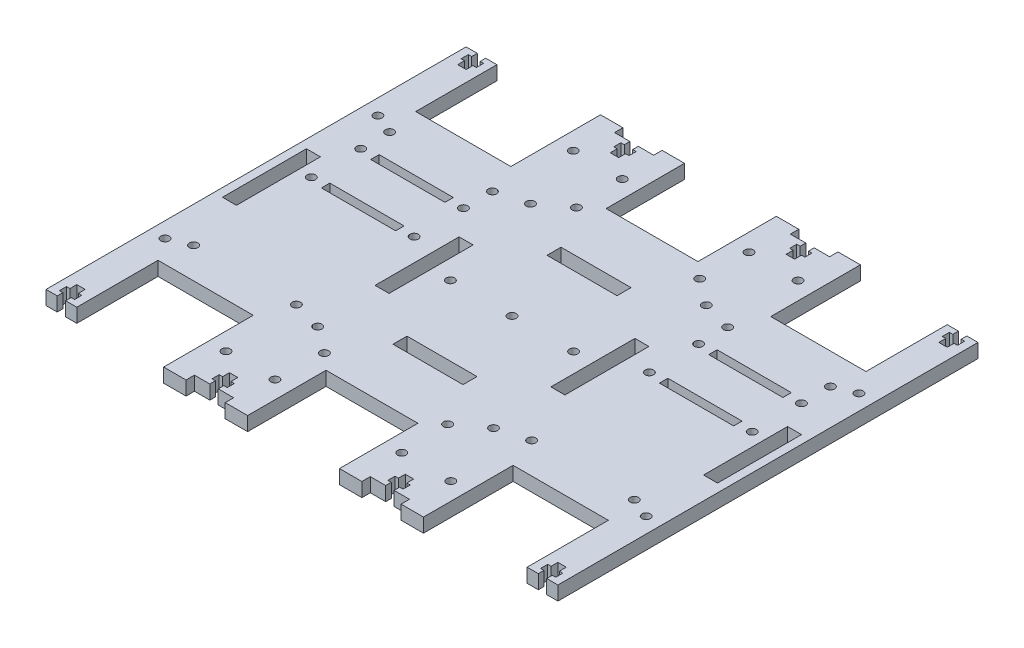
SolidWorks part; units mm, degrees
ref_plane "Front Plane" through (0, 0, 0) normal (0, 0, 1) x (1, 0, 0)
ref_plane "Top Plane" through (0, 0, 0) normal (0, 1, 0) x (1, 0, 0)
ref_plane "Right Plane" through (0, 0, 0) normal (1, 0, 0) x (0, 0, -1)
sketch "Sketch1" plane through (0, 0, 0) normal (0, 0, 1) x (1, 0, 0)
  line L0 (-91.394, 32.0854) -> (-91.394, 72.0854) construction
  line L1 (-91.394, 62.0854) -> (-80.394, 62.0854)
  line L2 (-91.394, 62.0854) -> (-91.394, 57.0854)
  line L3 (-91.394, 57.0854) -> (-80.394, 57.0854)
  line L4 (-80.394, 62.0854) -> (-80.394, 57.0854)
  line L5 (91.394, 72.0854) -> (91.394, 32.0854) construction
  line L6 (-46.394, 62.0854) -> (-16.394, 62.0854)
  line L7 (-46.394, 62.0854) -> (-46.394, 57.0854)
  line L8 (-46.394, 57.0854) -> (-16.394, 57.0854)
  line L9 (-16.394, 62.0854) -> (-16.394, 57.0854)
  line L10 (16.394, 62.0854) -> (46.394, 62.0854)
  line L11 (16.394, 62.0854) -> (16.394, 57.0854)
  line L12 (16.394, 57.0854) -> (46.394, 57.0854)
  line L13 (46.394, 62.0854) -> (46.394, 57.0854)
  line L14 (80.394, 62.0854) -> (91.394, 62.0854)
  line L15 (80.394, 62.0854) -> (80.394, 57.0854)
  line L16 (80.394, 57.0854) -> (91.394, 57.0854)
  line L17 (91.394, 62.0854) -> (91.394, 57.0854)
  line L18 (-80.394, 62.0854) -> (-46.394, 62.0854) construction
  line L19 (-16.394, 62.0854) -> (16.394, 62.0854) construction
  line L20 (46.394, 62.0854) -> (80.394, 62.0854) construction
  line L21 (-91.394, 72.0854) -> (91.394, 72.0854) construction
  line L22 (0, 72.0854) -> (0, 62.0854) construction
  dimension "D1" = 5
  dimension "D2" = 11
  dimension "D3" = 10
  dimension "D4" = 34
  dimension "D5" = 30
extrude "Boss-Extrude1" add sketch "Sketch1" along normal blind 25
sketch "Sketch2" plane through (0, 0, 25) normal (0, 0, 1) x (1, 0, 0)
  line L1 (-91.394, 62.0854) -> (91.394, 62.0854)
  line L2 (-91.394, 62.0854) -> (-91.394, 57.0854)
  line L3 (-91.394, 57.0854) -> (91.394, 57.0854)
  line L4 (91.394, 62.0854) -> (91.394, 57.0854)
extrude "Boss-Extrude4" add sketch "Sketch2" along normal blind 100
sketch "Sketch3" plane through (0, 0, 125) normal (0, 0, 1) x (1, 0, 0)
  line L4 (46.394, 62.0854) -> (16.394, 62.0854)
  line L5 (46.394, 57.0854) -> (46.394, 62.0854)
  line L6 (16.394, 57.0854) -> (46.394, 57.0854)
  line L7 (16.394, 62.0854) -> (16.394, 57.0854)
  line L8 (46.394, 62.0854) -> (16.394, 62.0854)
  line L9 (46.394, 57.0854) -> (46.394, 62.0854)
  line L10 (16.394, 57.0854) -> (46.394, 57.0854)
  line L11 (16.394, 62.0854) -> (16.394, 57.0854)
  line L12 (-16.394, 62.0854) -> (-46.394, 62.0854)
  line L13 (-16.394, 57.0854) -> (-16.394, 62.0854)
  line L14 (-46.394, 57.0854) -> (-16.394, 57.0854)
  line L15 (-46.394, 62.0854) -> (-46.394, 57.0854)
  line L16 (-16.394, 62.0854) -> (-46.394, 62.0854)
  line L17 (-16.394, 57.0854) -> (-16.394, 62.0854)
  line L18 (-46.394, 57.0854) -> (-16.394, 57.0854)
  line L19 (-46.394, 62.0854) -> (-46.394, 57.0854)
  line L20 (-80.394, 62.0854) -> (-91.394, 62.0854)
  line L21 (-80.394, 57.0854) -> (-80.394, 62.0854)
  line L22 (-91.394, 57.0854) -> (-80.394, 57.0854)
  line L23 (-91.394, 62.0854) -> (-91.394, 57.0854)
  line L24 (-80.394, 62.0854) -> (-91.394, 62.0854)
  line L25 (-80.394, 57.0854) -> (-80.394, 62.0854)
  line L26 (-91.394, 57.0854) -> (-80.394, 57.0854)
  line L27 (-91.394, 62.0854) -> (-91.394, 57.0854)
  line L28 (91.394, 62.0854) -> (80.394, 62.0854)
  line L29 (80.394, 62.0854) -> (80.394, 57.0854)
  line L30 (80.394, 57.0854) -> (91.394, 57.0854)
  line L31 (91.394, 57.0854) -> (91.394, 62.0854)
  line L32 (91.394, 62.0854) -> (80.394, 62.0854)
  line L33 (80.394, 62.0854) -> (80.394, 57.0854)
  line L34 (80.394, 57.0854) -> (91.394, 57.0854)
  line L35 (91.394, 57.0854) -> (91.394, 62.0854)
  dimension "D1" = 0
  dimension "D2" = 0
  dimension "D3" = 0
  dimension "D4" = 0
extrude "Boss-Extrude5" add sketch "Sketch3" along normal blind 25
sketch "Sketch4" plane through (0, 62.0854, 0) normal (0, 1, 0) x (1, 0, 0)
  line L0 (85.894, 0) -> (85.894, -12.8544) construction
  line L1 (91.394, 0) -> (80.394, 0) construction
  line L2 (84.394, -2) -> (83.169, -2)
  line L3 (87.394, -7) -> (84.394, -7)
  line L4 (87.394, -7) -> (87.394, -4.55)
  line L5 (87.394, 0) -> (84.394, 0)
  line L6 (84.394, -7) -> (84.394, -4.55)
  line L7 (87.394, -7) -> (84.394, 0) construction
  line L8 (87.394, 0) -> (84.394, -7) construction
  line L9 (88.619, -2) -> (87.394, -2)
  line L10 (88.619, -2) -> (88.619, -4.55)
  line L11 (88.619, -4.55) -> (87.394, -4.55)
  line L12 (83.169, -2) -> (83.169, -4.55)
  line L13 (88.619, -2) -> (83.169, -4.55) construction
  line L14 (88.619, -4.55) -> (83.169, -2) construction
  line L15 (84.394, -2) -> (84.394, 0)
  line L16 (84.394, -4.55) -> (83.169, -4.55)
  line L17 (87.394, -2) -> (87.394, 0)
  line L18 (31.394, 0) -> (31.394, -22.5129) construction
  line L19 (46.394, 0) -> (16.394, 0) construction
  line L20 (85.894, -12.8544) -> (31.394, -12.8544) construction
  line L21 (58.644, -12.8544) -> (58.644, 12.1198) construction
  line L22 (28.669, -4.55) -> (34.119, -2) construction
  line L23 (28.669, -2) -> (34.119, -4.55) construction
  line L24 (29.894, 0) -> (32.894, -7) construction
  line L25 (29.894, -7) -> (32.894, 0) construction
  line L26 (29.894, -2) -> (29.894, 0)
  line L27 (32.894, -4.55) -> (34.119, -4.55)
  line L28 (32.894, -2) -> (32.894, 0)
  line L29 (34.119, -2) -> (34.119, -4.55)
  line L30 (28.669, -4.55) -> (29.894, -4.55)
  line L31 (28.669, -2) -> (28.669, -4.55)
  line L32 (28.669, -2) -> (29.894, -2)
  line L33 (32.894, -7) -> (32.894, -4.55)
  line L34 (29.894, 0) -> (32.894, 0)
  line L35 (29.894, -7) -> (29.894, -4.55)
  line L36 (29.894, -7) -> (32.894, -7)
  line L37 (32.894, -2) -> (34.119, -2)
  line L38 (0, -25) -> (0, 26.5312) construction
  line L39 (16.394, -25) -> (-16.394, -25) construction
  line L40 (-88.619, -4.55) -> (-83.169, -2) construction
  line L41 (-88.619, -2) -> (-83.169, -4.55) construction
  line L42 (-87.394, 0) -> (-84.394, -7) construction
  line L43 (-87.394, -7) -> (-84.394, 0) construction
  line L44 (-87.394, -2) -> (-87.394, 0)
  line L45 (-84.394, -4.55) -> (-83.169, -4.55)
  line L46 (-84.394, -2) -> (-84.394, 0)
  line L47 (-83.169, -2) -> (-83.169, -4.55)
  line L48 (-88.619, -4.55) -> (-87.394, -4.55)
  line L49 (-88.619, -2) -> (-88.619, -4.55)
  line L50 (-88.619, -2) -> (-87.394, -2)
  line L51 (-84.394, -7) -> (-84.394, -4.55)
  line L52 (-87.394, 0) -> (-84.394, 0)
  line L53 (-87.394, -7) -> (-87.394, -4.55)
  line L54 (-87.394, -7) -> (-84.394, -7)
  line L55 (-84.394, -2) -> (-83.169, -2)
  line L56 (-29.894, -7) -> (-32.894, 0) construction
  line L57 (-29.894, 0) -> (-32.894, -7) construction
  line L58 (-28.669, -2) -> (-34.119, -4.55) construction
  line L59 (-28.669, -4.55) -> (-34.119, -2) construction
  line L60 (-32.894, -2) -> (-34.119, -2)
  line L61 (-29.894, -7) -> (-32.894, -7)
  line L62 (-29.894, -7) -> (-29.894, -4.55)
  line L63 (-29.894, 0) -> (-32.894, 0)
  line L64 (-32.894, -7) -> (-32.894, -4.55)
  line L65 (-28.669, -2) -> (-29.894, -2)
  line L66 (-28.669, -2) -> (-28.669, -4.55)
  line L67 (-28.669, -4.55) -> (-29.894, -4.55)
  line L68 (-34.119, -2) -> (-34.119, -4.55)
  line L69 (-32.894, -2) -> (-32.894, 0)
  line L70 (-32.894, -4.55) -> (-34.119, -4.55)
  line L71 (-29.894, -2) -> (-29.894, 0)
  line L72 (91.394, -75) -> (-91.394, -75) construction
  line L73 (91.394, -150) -> (91.394, 0) construction
  line L74 (-91.394, -150) -> (-91.394, 0) construction
  line L75 (-28.669, -145.45) -> (-34.119, -148) construction
  line L76 (-28.669, -148) -> (-34.119, -145.45) construction
  line L77 (-29.894, -150) -> (-32.894, -143) construction
  line L78 (-29.894, -143) -> (-32.894, -150) construction
  line L79 (-87.394, -143) -> (-84.394, -150) construction
  line L80 (-87.394, -150) -> (-84.394, -143) construction
  line L81 (-88.619, -148) -> (-83.169, -145.45) construction
  line L82 (-88.619, -145.45) -> (-83.169, -148) construction
  line L83 (29.894, -143) -> (32.894, -150) construction
  line L84 (29.894, -150) -> (32.894, -143) construction
  line L85 (28.669, -148) -> (34.119, -145.45) construction
  line L86 (28.669, -145.45) -> (34.119, -148) construction
  line L87 (85.894, -137.1456) -> (31.394, -137.1456) construction
  line L88 (88.619, -145.45) -> (83.169, -148) construction
  line L89 (88.619, -148) -> (83.169, -145.45) construction
  line L90 (87.394, -150) -> (84.394, -143) construction
  line L91 (87.394, -143) -> (84.394, -150) construction
  line L92 (85.894, -150) -> (85.894, -137.1456) construction
  line L93 (-29.894, -148) -> (-29.894, -150)
  line L94 (-32.894, -145.45) -> (-34.119, -145.45)
  line L95 (-32.894, -148) -> (-32.894, -150)
  line L96 (-34.119, -148) -> (-34.119, -145.45)
  line L97 (-28.669, -145.45) -> (-29.894, -145.45)
  line L98 (-28.669, -148) -> (-28.669, -145.45)
  line L99 (-28.669, -148) -> (-29.894, -148)
  line L100 (-32.894, -143) -> (-32.894, -145.45)
  line L101 (-29.894, -150) -> (-32.894, -150)
  line L102 (-29.894, -143) -> (-29.894, -145.45)
  line L103 (-29.894, -143) -> (-32.894, -143)
  line L104 (-32.894, -148) -> (-34.119, -148)
  line L105 (-84.394, -148) -> (-83.169, -148)
  line L106 (-87.394, -143) -> (-84.394, -143)
  line L107 (-87.394, -143) -> (-87.394, -145.45)
  line L108 (-87.394, -150) -> (-84.394, -150)
  line L109 (-84.394, -143) -> (-84.394, -145.45)
  line L110 (-88.619, -148) -> (-87.394, -148)
  line L111 (-88.619, -148) -> (-88.619, -145.45)
  line L112 (-88.619, -145.45) -> (-87.394, -145.45)
  line L113 (-83.169, -148) -> (-83.169, -145.45)
  line L114 (-84.394, -148) -> (-84.394, -150)
  line L115 (-84.394, -145.45) -> (-83.169, -145.45)
  line L116 (-87.394, -148) -> (-87.394, -150)
  line L117 (32.894, -148) -> (34.119, -148)
  line L118 (29.894, -143) -> (32.894, -143)
  line L119 (29.894, -143) -> (29.894, -145.45)
  line L120 (29.894, -150) -> (32.894, -150)
  line L121 (32.894, -143) -> (32.894, -145.45)
  line L122 (28.669, -148) -> (29.894, -148)
  line L123 (28.669, -148) -> (28.669, -145.45)
  line L124 (28.669, -145.45) -> (29.894, -145.45)
  line L125 (34.119, -148) -> (34.119, -145.45)
  line L126 (32.894, -148) -> (32.894, -150)
  line L127 (32.894, -145.45) -> (34.119, -145.45)
  line L128 (29.894, -148) -> (29.894, -150)
  line L129 (87.394, -148) -> (87.394, -150)
  line L130 (84.394, -145.45) -> (83.169, -145.45)
  line L131 (84.394, -148) -> (84.394, -150)
  line L132 (83.169, -148) -> (83.169, -145.45)
  line L133 (88.619, -145.45) -> (87.394, -145.45)
  line L134 (88.619, -148) -> (88.619, -145.45)
  line L135 (88.619, -148) -> (87.394, -148)
  line L136 (84.394, -143) -> (84.394, -145.45)
  line L137 (87.394, -150) -> (84.394, -150)
  line L138 (87.394, -143) -> (87.394, -145.45)
  line L139 (87.394, -143) -> (84.394, -143)
  line L140 (84.394, -148) -> (83.169, -148)
  point P4 (85.894, -3.5)
  point P9 (85.894, -3.275)
  point P37 (31.394, -3.275)
  point P38 (31.394, -3.5)
  point P56 (-85.894, -3.275)
  point P57 (-85.894, -3.5)
  point P70 (-31.394, -3.5)
  point P71 (-31.394, -3.275)
  point P129 (-31.394, -146.725)
  point P130 (-31.394, -146.5)
  point P131 (-85.894, -146.5)
  point P132 (-85.894, -146.725)
  point P133 (31.394, -146.5)
  point P134 (31.394, -146.725)
  point P135 (85.894, -146.725)
  point P136 (85.894, -146.5)
  dimension "D1" = 7
  dimension "D2" = 3
  dimension "D3" = 5.45
  dimension "D4" = 2.55
  dimension "D5" = 2
extrude "Cut-Extrude1" cut sketch "Sketch4" against normal through all
sketch "Sketch5" plane through (0, 0, 0) normal (0, 0, -1) x (-1, 0, 0)
  line L0 (-32.894, 57.0854) -> (-46.394, 57.0854) construction
  line L1 (-46.394, 62.0854) -> (-38.394, 62.0854)
  line L2 (-46.394, 62.0854) -> (-46.394, 57.0854)
  line L3 (-46.394, 57.0854) -> (-38.394, 57.0854)
  line L4 (-38.394, 62.0854) -> (-38.394, 57.0854)
  line L5 (46.394, 57.0854) -> (32.894, 57.0854) construction
  line L6 (-16.394, 62.0854) -> (-24.394, 62.0854)
  line L7 (-16.394, 62.0854) -> (-16.394, 57.0854)
  line L8 (-16.394, 57.0854) -> (-24.394, 57.0854)
  line L9 (-24.394, 62.0854) -> (-24.394, 57.0854)
  line L10 (16.394, 62.0854) -> (24.394, 62.0854)
  line L11 (16.394, 62.0854) -> (16.394, 57.0854)
  line L12 (16.394, 57.0854) -> (24.394, 57.0854)
  line L13 (24.394, 62.0854) -> (24.394, 57.0854)
  line L14 (46.394, 62.0854) -> (38.394, 62.0854)
  line L15 (46.394, 62.0854) -> (46.394, 57.0854)
  line L16 (46.394, 57.0854) -> (38.394, 57.0854)
  line L17 (38.394, 62.0854) -> (38.394, 57.0854)
  line L18 (29.894, 57.0854) -> (16.394, 57.0854) construction
  line L19 (-16.394, 57.0854) -> (-29.894, 57.0854) construction
  dimension "D1" = 8
  dimension "D2" = 8
extrude "Boss-Extrude6" add sketch "Sketch5" along normal blind 3
sketch "Sketch6" plane through (0, 0, 150) normal (0, 0, 1) x (1, 0, 0)
  line L4 (-16.394, 62.0854) -> (-24.394, 62.0854)
  line L5 (-24.394, 62.0854) -> (-24.394, 57.0854)
  line L6 (-24.394, 57.0854) -> (-16.394, 57.0854)
  line L7 (-16.394, 57.0854) -> (-16.394, 62.0854)
  line L8 (-16.394, 62.0854) -> (-24.394, 62.0854)
  line L9 (-24.394, 62.0854) -> (-24.394, 57.0854)
  line L10 (-24.394, 57.0854) -> (-16.394, 57.0854)
  line L11 (-16.394, 57.0854) -> (-16.394, 62.0854)
  line L12 (24.394, 62.0854) -> (16.394, 62.0854)
  line L13 (24.394, 57.0854) -> (24.394, 62.0854)
  line L14 (16.394, 57.0854) -> (24.394, 57.0854)
  line L15 (16.394, 62.0854) -> (16.394, 57.0854)
  line L16 (24.394, 62.0854) -> (16.394, 62.0854)
  line L17 (24.394, 57.0854) -> (24.394, 62.0854)
  line L18 (16.394, 57.0854) -> (24.394, 57.0854)
  line L19 (16.394, 62.0854) -> (16.394, 57.0854)
  line L20 (46.394, 62.0854) -> (38.394, 62.0854)
  line L21 (38.394, 62.0854) -> (38.394, 57.0854)
  line L22 (38.394, 57.0854) -> (46.394, 57.0854)
  line L23 (46.394, 57.0854) -> (46.394, 62.0854)
  line L24 (46.394, 62.0854) -> (38.394, 62.0854)
  line L25 (38.394, 62.0854) -> (38.394, 57.0854)
  line L26 (38.394, 57.0854) -> (46.394, 57.0854)
  line L27 (46.394, 57.0854) -> (46.394, 62.0854)
  line L28 (-38.394, 62.0854) -> (-46.394, 62.0854)
  line L29 (-38.394, 57.0854) -> (-38.394, 62.0854)
  line L30 (-46.394, 57.0854) -> (-38.394, 57.0854)
  line L31 (-46.394, 62.0854) -> (-46.394, 57.0854)
  line L32 (-38.394, 62.0854) -> (-46.394, 62.0854)
  line L33 (-38.394, 57.0854) -> (-38.394, 62.0854)
  line L34 (-46.394, 57.0854) -> (-38.394, 57.0854)
  line L35 (-46.394, 62.0854) -> (-46.394, 57.0854)
  dimension "D1" = 0
  dimension "D2" = 0
  dimension "D3" = 0
  dimension "D4" = 0
extrude "Boss-Extrude7" add sketch "Sketch6" along normal blind 3
sketch "Sketch7" plane through (0, 62.0854, 0) normal (0, 1, 0) x (1, 0, 0)
  line L4 (83.394, -60) -> (83.394, -90)
  line L5 (83.394, -90) -> (88.394, -90)
  line L6 (88.394, -90) -> (88.394, -60)
  line L7 (88.394, -60) -> (83.394, -60)
  line L8 (83.394, -60) -> (83.394, -90)
  line L9 (83.394, -90) -> (88.394, -90)
  line L10 (88.394, -90) -> (88.394, -60)
  line L11 (88.394, -60) -> (83.394, -60)
  line L12 (-83.394, -90) -> (-83.394, -60)
  line L13 (-83.394, -60) -> (-88.394, -60)
  line L14 (-88.394, -60) -> (-88.394, -90)
  line L15 (-88.394, -90) -> (-83.394, -90)
  line L16 (-83.394, -90) -> (-83.394, -60)
  line L17 (-83.394, -60) -> (-88.394, -60)
  line L18 (-88.394, -60) -> (-88.394, -90)
  line L19 (-88.394, -90) -> (-83.394, -90)
  dimension "D1" = 0
  dimension "D2" = 0
extrude "Cut-Extrude2" cut sketch "Sketch7" against normal through all
sketch "Sketch8" plane through (0, 62.0854, 0) normal (0, 1, 0) x (1, 0, 0)
  line L0 (-83.394, -35.5) -> (-88.394, -35.5) construction
  line L1 (-83.394, -38.5) -> (-88.394, -38.5) construction
  line L2 (-83.394, -35.5) -> (-88.394, -35.5) construction
  line L3 (-83.394, -38.5) -> (-88.394, -38.5) construction
  line L4 (-85.894, -38.5) -> (-85.894, -35.5) construction
  line L5 (-83.394, -75) -> (83.394, -75) construction
  line L6 (-83.394, -90) -> (-83.394, -60) construction
  line L7 (83.394, -60) -> (83.394, -90) construction
  line L8 (0, -125) -> (0, -25) construction
  line L9 (16.394, -125) -> (-16.394, -125) construction
  line L10 (16.394, -25) -> (-16.394, -25) construction
  line L11 (85.894, -38.5) -> (85.894, -35.5) construction
  line L12 (83.394, -38.5) -> (88.394, -38.5) construction
  line L13 (83.394, -35.5) -> (88.394, -35.5) construction
  circle A0 centre (-85.894, -37) radius 1.5
  circle A1 centre (-85.894, -113) radius 1.5
  circle A2 centre (85.894, -113) radius 1.5
  circle A3 centre (85.894, -37) radius 1.5
extrude "Cut-Extrude3" cut sketch "Sketch8" against normal through all
sketch "Sketch9" plane through (0, 62.0854, 0) normal (0, 1, 0) x (1, 0, 0)
  line L0 (-83.394, -38.5) -> (-33.894, -38.5) construction
  line L1 (-58.644, -38.5) -> (-58.644, -94.7592) construction
  line L2 (-33.894, -75) -> (-58.644, -75) construction
  line L3 (-28.894, -75) -> (28.894, -75) construction
  line L4 (-33.894, -60) -> (-33.894, -90)
  line L5 (-33.894, -90) -> (-28.894, -90)
  line L6 (-28.894, -90) -> (-28.894, -60)
  line L7 (-28.894, -60) -> (-33.894, -60)
  line L8 (-33.894, -60) -> (-33.894, -90)
  line L9 (-33.894, -90) -> (-28.894, -90)
  line L10 (-28.894, -90) -> (-28.894, -60)
  line L11 (-28.894, -60) -> (-33.894, -60)
  line L12 (28.894, -90) -> (28.894, -60) construction
  line L13 (0, -75) -> (0, -41.0499) construction
  line L14 (28.894, -60) -> (33.894, -60)
  line L15 (33.894, -60) -> (33.894, -90)
  line L16 (28.894, -90) -> (28.894, -60)
  line L17 (33.894, -90) -> (28.894, -90)
  circle A0 centre (-85.894, -37) radius 1.5 construction
  circle A1 centre (-85.894, -37) radius 1.5 construction
  circle A2 centre (-31.394, -37) radius 1.5
  circle A3 centre (-31.394, -113) radius 1.5
  circle A4 centre (31.394, -113) radius 1.5
  circle A5 centre (31.394, -37) radius 1.5
  dimension "D1" = 0
extrude "Cut-Extrude4" cut sketch "Sketch9" against normal through all
sketch "Sketch10" plane through (0, 62.0854, 0) normal (0, 1, 0) x (1, 0, 0)
  line L0 (46.394, -25) -> (46.394, 3) construction
  line L1 (80.394, -29) -> (46.394, -29)
  line L2 (80.394, -29) -> (80.394, -24)
  line L3 (80.394, -24) -> (46.394, -24)
  line L4 (46.394, -29) -> (46.394, -24)
  line L5 (80.394, -24) -> (46.394, -24) construction
  line L6 (83.394, -75) -> (0, -75) construction
  line L7 (83.394, -60) -> (83.394, -90) construction
  line L8 (0, -75) -> (0, -125) construction
  line L9 (16.394, -125) -> (-16.394, -125) construction
  line L10 (80.394, -121) -> (80.394, -126)
  line L11 (80.394, -126) -> (46.394, -126)
  line L12 (46.394, -121) -> (46.394, -126)
  line L13 (80.394, -121) -> (46.394, -121)
  line L14 (-80.394, -29) -> (-80.394, -24)
  line L15 (-80.394, -24) -> (-46.394, -24)
  line L16 (-46.394, -29) -> (-46.394, -24)
  line L17 (-80.394, -29) -> (-46.394, -29)
  line L18 (-80.394, -121) -> (-80.394, -126)
  line L19 (-80.394, -121) -> (-46.394, -121)
  line L20 (-46.394, -121) -> (-46.394, -126)
  line L21 (-80.394, -126) -> (-46.394, -126)
extrude "Cut-Extrude5" cut sketch "Sketch10" against normal blind 5
sketch "Sketch11" plane through (0, 62.0854, 0) normal (0, 1, 0) x (1, 0, 0)
  line L4 (-12.5, -50) -> (12.5, -50)
  line L5 (12.5, -50) -> (12.5, -45)
  line L6 (12.5, -45) -> (-12.5, -45)
  line L7 (-12.5, -45) -> (-12.5, -50)
  line L8 (-12.5, -50) -> (12.5, -50)
  line L9 (12.5, -50) -> (12.5, -45)
  line L10 (12.5, -45) -> (-12.5, -45)
  line L11 (-12.5, -45) -> (-12.5, -50)
  line L13 (12.5, -100) -> (-12.5, -100)
  line L14 (-12.5, -100) -> (-12.5, -105)
  line L15 (-12.5, -105) -> (12.5, -105)
  line L16 (12.5, -105) -> (12.5, -100)
  line L17 (12.5, -100) -> (-12.5, -100)
  line L18 (-12.5, -100) -> (-12.5, -105)
  line L19 (-12.5, -105) -> (12.5, -105)
  line L20 (12.5, -105) -> (12.5, -100)
  dimension "D1" = 0
  dimension "D2" = 0
extrude "Cut-Extrude6" cut sketch "Sketch11" against normal through all
sketch "Sketch12" plane through (0, 62.0854, 0) normal (0, 1, 0) x (1, 0, 0)
  line L0 (-40.494, -69.45) -> (-43.494, -69.45) construction
  line L1 (-40.494, -66.45) -> (-43.494, -66.45) construction
  line L2 (-40.494, -69.45) -> (-43.494, -69.45) construction
  line L3 (-40.494, -66.45) -> (-43.494, -66.45) construction
  line L4 (-80.194, -66.45) -> (-77.194, -66.45) construction
  line L5 (-80.194, -69.45) -> (-77.194, -69.45) construction
  line L6 (-80.194, -66.45) -> (-77.194, -66.45) construction
  line L7 (-80.194, -69.45) -> (-77.194, -69.45) construction
  line L8 (47.094, -48.85) -> (47.094, -51.85)
  line L9 (-41.994, -66.45) -> (-41.994, -69.45) construction
  line L10 (-78.694, -66.45) -> (-78.694, -69.45) construction
  line L11 (-71.594, -51.85) -> (-73.594, -51.85) construction
  line L12 (-71.594, -48.35) -> (-71.594, -53.65) construction
  line L13 (-47.094, -66.45) -> (-73.594, -66.45)
  line L14 (-47.094, -69.45) -> (-47.094, -66.45)
  line L15 (-73.594, -69.45) -> (-47.094, -69.45)
  line L16 (-73.594, -66.45) -> (-73.594, -69.45)
  line L17 (-47.094, -66.45) -> (-73.594, -66.45)
  line L18 (-47.094, -69.45) -> (-47.094, -66.45)
  line L19 (-73.594, -69.45) -> (-47.094, -69.45)
  line L20 (-73.594, -66.45) -> (-73.594, -69.45)
  line L21 (-73.594, -51.85) -> (-73.594, -66.45) construction
  line L22 (-49.944, -48.35) -> (-70.744, -48.35) construction
  line L23 (-73.594, -59.15) -> (-78.2524, -59.15) construction
  line L24 (-78.694, -51.85) -> (-78.694, -48.85) construction
  line L25 (-41.994, -51.85) -> (-41.994, -48.85) construction
  line L26 (-80.194, -48.85) -> (-77.194, -48.85) construction
  line L27 (-80.194, -51.85) -> (-77.194, -51.85) construction
  line L28 (-40.494, -51.85) -> (-43.494, -51.85) construction
  line L29 (-40.494, -48.85) -> (-43.494, -48.85) construction
  line L30 (-73.594, -51.85) -> (-73.594, -48.85)
  line L31 (-73.594, -48.85) -> (-47.094, -48.85)
  line L32 (-47.094, -48.85) -> (-47.094, -51.85)
  line L33 (-47.094, -51.85) -> (-73.594, -51.85)
  line L34 (0, -25) -> (0, -125) construction
  line L35 (16.394, -25) -> (-16.394, -25) construction
  line L36 (16.394, -125) -> (-16.394, -125) construction
  line L37 (73.594, -48.85) -> (47.094, -48.85)
  line L38 (73.594, -51.85) -> (73.594, -48.85)
  line L39 (47.094, -51.85) -> (73.594, -51.85)
  line L40 (73.594, -66.45) -> (73.594, -69.45)
  line L41 (47.094, -66.45) -> (73.594, -66.45)
  line L42 (47.094, -69.45) -> (47.094, -66.45)
  line L43 (73.594, -69.45) -> (47.094, -69.45)
  circle A0 centre (-41.994, -67.95) radius 1.5
  circle A1 centre (-78.694, -67.95) radius 1.5
  circle A2 centre (-78.694, -50.35) radius 1.5
  circle A3 centre (-41.994, -50.35) radius 1.5
  circle A4 centre (41.994, -67.95) radius 1.5
  circle A5 centre (78.694, -67.95) radius 1.5
  circle A6 centre (41.994, -50.35) radius 1.5
  circle A7 centre (78.694, -50.35) radius 1.5
  dimension "D2" = 3.5
  dimension "D1" = 0
extrude "Cut-Extrude7" cut sketch "Sketch12" against normal through all
sketch "Sketch14" plane through (0, 57.0854, 0) normal (0, -1, 0) x (1, 0, 0)
  line L0 (91.394, 75) -> (-91.394, 75) construction
  line L1 (91.394, 150) -> (91.394, 0) construction
  line L2 (-91.394, 150) -> (-91.394, 0) construction
  line L3 (91.394, 30) -> (-91.394, 30) construction
  line L4 (0, 75) -> (0, 30) construction
  line L5 (-22, 30) -> (-22, 75) construction
  line L6 (91.394, 40) -> (-91.394, 40) construction
  line L7 (41.994, 40) -> (41.994, 50.35) construction
  line L8 (78.694, 40) -> (78.694, 50.35) construction
  circle A0 centre (0, 75) radius 1.5
  circle A2 centre (-22, 75) radius 1.5
  circle A4 centre (-22, 30) radius 1.5
  circle A5 centre (22, 75) radius 1.5
  circle A6 centre (22, 30) radius 1.5
  circle A7 centre (-22, 120) radius 1.5
  circle A8 centre (22, 120) radius 1.5
  circle A9 centre (41.994, 40) radius 1.5
  circle A10 centre (78.694, 40) radius 1.5
  circle A12 centre (41.994, 110) radius 1.5
  circle A13 centre (78.694, 110) radius 1.5
  circle A14 centre (-41.994, 110) radius 1.5
  circle A15 centre (-78.694, 110) radius 1.5
  circle A16 centre (-41.994, 40) radius 1.5
  circle A17 centre (-78.694, 40) radius 1.5
  dimension "D2" = 3
  dimension "D1" = 45
  dimension "D3" = 22
  dimension "D4" = 35
extrude "Cut-Extrude8" cut sketch "Sketch14" against normal through all
sketch "Sketch15" plane through (0, 57.0854, 0) normal (0, -1, 0) x (1, 0, 0)
  line L0 (46.394, 13) -> (-46.394, 13) construction
  line L1 (46.394, 29) -> (46.394, -3) construction
  line L2 (-46.394, 29) -> (-46.394, -3) construction
  line L3 (-91.394, 75) -> (102.3105, 75) construction
  line L4 (-91.394, 150) -> (-91.394, 0) construction
  line L5 (33.894, 13) -> (40.144, 29) construction
  line L6 (83.394, 29) -> (33.894, 29) construction
  line L7 (40.144, 29) -> (46.394, 13) construction
  line L8 (40.144, 29) -> (40.144, 13) construction
  line L9 (31.394, 10) -> (31.394, 19) construction
  line L10 (28.894, 10) -> (33.894, 10) construction
  line L11 (28.894, 19) -> (33.894, 19) construction
  line L12 (33.894, 19) -> (33.894, -3) construction
  line L13 (0, 75) -> (0, 13) construction
  circle A0 centre (40.144, 13) radius 1.5
  circle A1 centre (22.644, 13) radius 1.5
  circle A2 centre (-22.644, 13) radius 1.5
  circle A3 centre (-40.144, 13) radius 1.5
  circle A4 centre (-40.144, 137) radius 1.5
  circle A5 centre (-22.644, 137) radius 1.5
  circle A6 centre (22.644, 137) radius 1.5
  circle A7 centre (40.144, 137) radius 1.5
  dimension "D1" = 3
extrude "Cut-Extrude9" cut sketch "Sketch15" against normal through all
